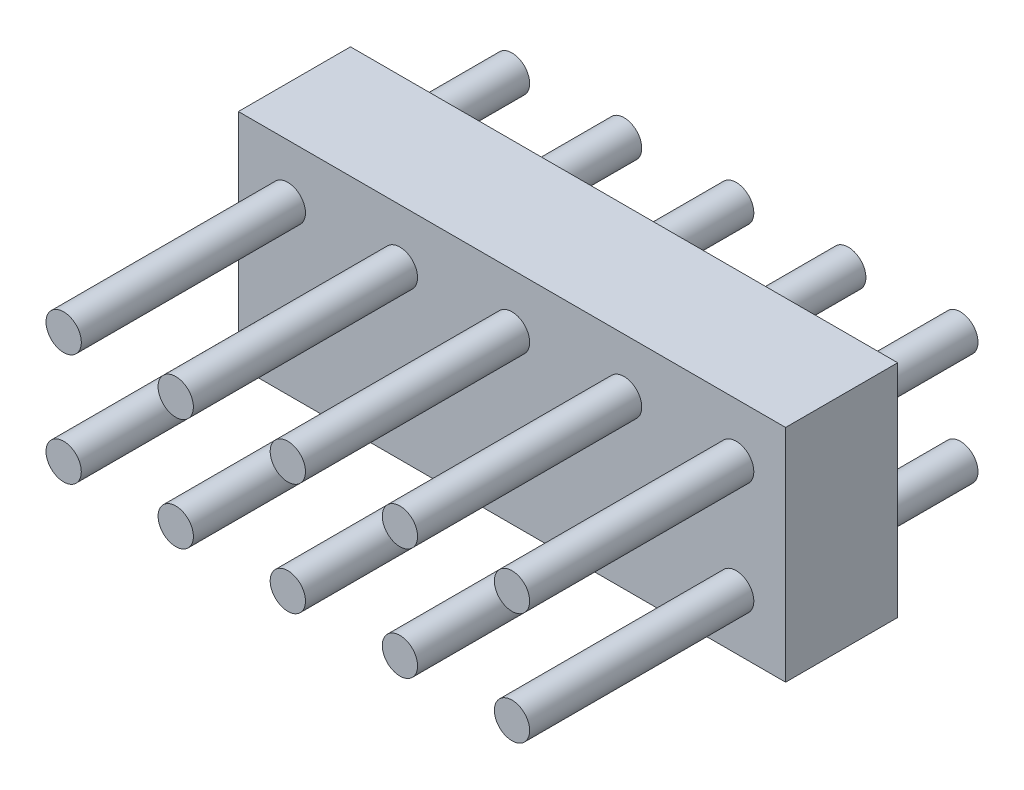
SolidWorks part; units mm, degrees
ref_plane "前视基准面" through (0, 0, 0) normal (0, 0, 1) x (1, 0, 0)
ref_plane "上视基准面" through (0, 0, 0) normal (0, 1, 0) x (1, 0, 0)
ref_plane "右视基准面" through (0, 0, 0) normal (1, 0, 0) x (0, 0, -1)
sketch "草图1" plane through (0, 0, 0) normal (0, 0, 1) x (1, 0, 0)
  line L1 (0, 0) -> (12.4, 0)
  line L2 (0, 0) -> (0, -5)
  line L3 (0, -5) -> (12.4, -5)
  line L4 (12.4, 0) -> (12.4, -5)
  dimension "D1" = 12.4
  dimension "D2" = 5
extrude "凸台-拉伸1" add sketch "草图1" along normal blind 2.54
sketch "草图2" plane through (0, 0, 2.54) normal (0, 0, 1) x (1, 0, 0)
  line L0 (0, -2.5) -> (12.4, -2.5) construction
  line L1 (0, 0) -> (0, -5) construction
  line L2 (12.4, -5) -> (12.4, 0) construction
  line L3 (6.2, 0) -> (6.2, -5) construction
  line L4 (12.4, 0) -> (0, 0) construction
  line L5 (0, -5) -> (12.4, -5) construction
  line L6 (0, -1.23) -> (12.4, -1.23) construction
  circle A0 centre (6.2, -1.23) radius 0.4
  circle A1 centre (8.74, -1.23) radius 0.4
  circle A2 centre (11.28, -1.23) radius 0.4
  circle A3 centre (1.12, -1.23) radius 0.4
  circle A4 centre (3.66, -1.23) radius 0.4
  circle A5 centre (11.28, -3.77) radius 0.4
  circle A6 centre (8.74, -3.77) radius 0.4
  circle A7 centre (6.2, -3.77) radius 0.4
  circle A8 centre (3.66, -3.77) radius 0.4
  circle A9 centre (1.12, -3.77) radius 0.4
  dimension "D1" = 0.8
  dimension "D2" = 3
extrude "凸台-拉伸2" add sketch "草图2" along normal mid plane 10.16
